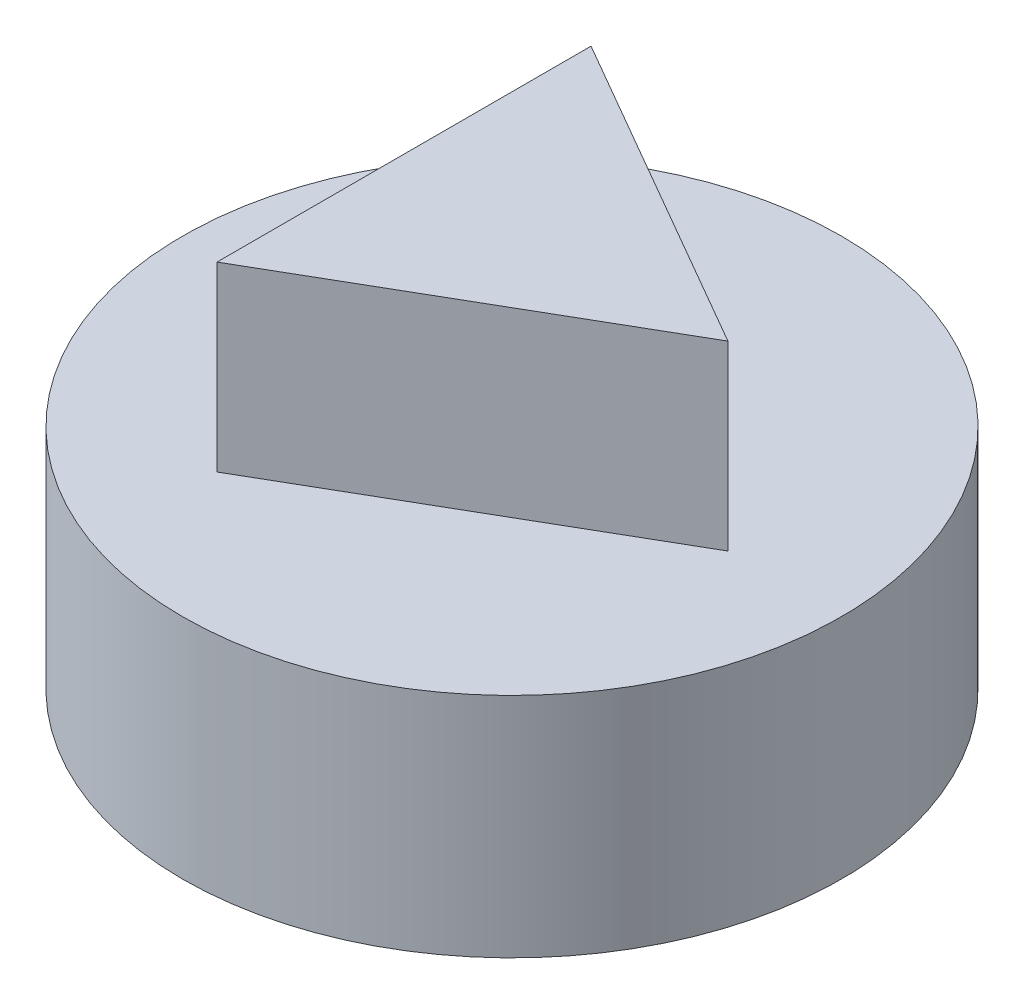
SolidWorks part; units mm, degrees
ref_plane "Front Plane" through (0, 0, 0) normal (0, 0, 1) x (1, 0, 0)
ref_plane "Top Plane" through (0, 0, 0) normal (0, 1, 0) x (1, 0, 0)
ref_plane "Right Plane" through (0, 0, 0) normal (1, 0, 0) x (0, 0, -1)
sketch "Sketch1" plane through (0, 0, 0) normal (0, 1, 0) x (1, 0, 0)
  circle A0 centre (0, 0) radius 7.25
extrude "Boss-Extrude1" add sketch "Sketch1" along normal blind 5
sketch "Sketch2" plane through (0, 5, 0) normal (0, 1, 0) x (1, 0, 0)
  line L1 (4.75, 0) -> (-2.375, 4.1136)
  line L2 (-2.375, 4.1136) -> (-2.375, -4.1136)
  line L3 (-2.375, -4.1136) -> (4.75, 0)
  arc A0 (-2.1226, 3.9679) -> (-2.375, 3.8222) centre (0, 0) ccw
  circle A1 centre (0, 0) radius 2.375 construction
  arc A2 (-2.375, -3.8222) -> (-2.1226, -3.9679) centre (0, 0) ccw
  arc A3 (4.4976, -0.1457) -> (4.4976, 0.1457) centre (0, 0) ccw
extrude "Boss-Extrude2" add sketch "Sketch2" along normal blind 4 contours L1 L2 L3
